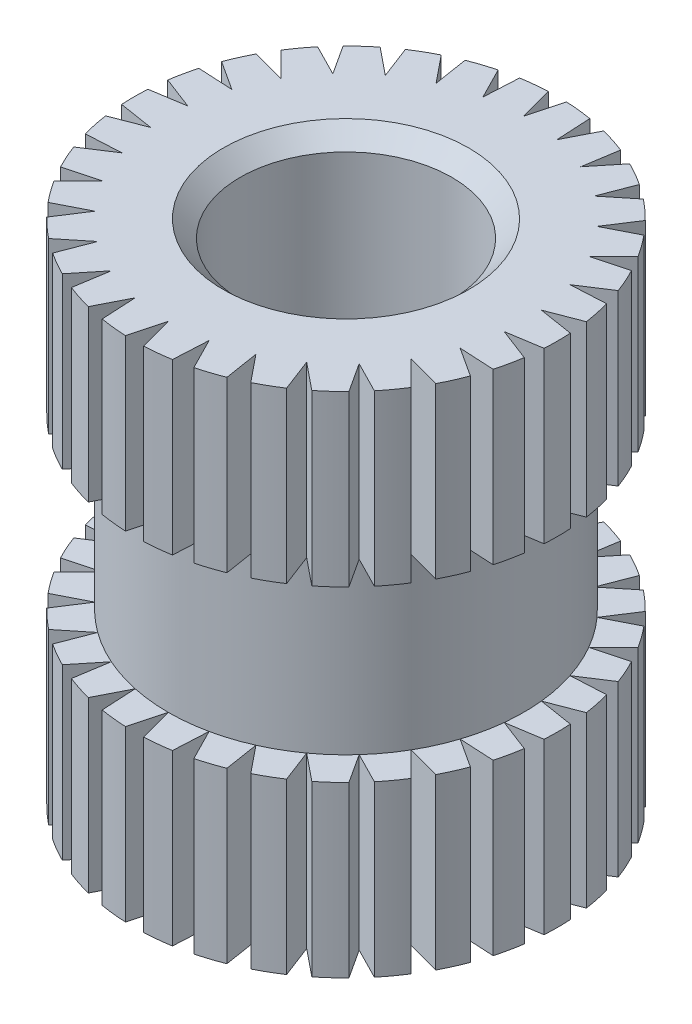
SolidWorks part; units mm, degrees
material "Brass"
ref_plane "Front" through (0, 0, 0) normal (0, 0, 1) x (1, 0, 0)
ref_plane "Top" through (0, 0, 0) normal (0, 1, 0) x (1, 0, 0)
ref_plane "Right" through (0, 0, 0) normal (1, 0, 0) x (0, 0, -1)
sketch "Sketch1" plane through (0, 0, 0) normal (1, 0, 0) x (0, 0, -1)
  line L0 (0, 5.7394) -> (0, 0) construction
  line L1 (0, 0) -> (3.7148, 0) construction
  line L2 (2.1, -1) -> (2.5, -1)
  line L3 (1.25, 3) -> (2.5, 3)
  line L4 (1.25, 3) -> (1.25, -3)
  line L5 (2.5, -3) -> (2.5, -1)
  line L6 (2.5, 3) -> (2.5, 1)
  line L7 (2.1, 1) -> (2.5, 1)
  line L8 (2.1, 1) -> (2.1, -1)
  line L9 (1.25, -3) -> (2.5, -3)
  point P10 (2.1, 0)
  point P14 (1.25, 0)
  dimension "D1" = 2.5
  dimension "D2" = 3
  dimension "D3" = 5
  dimension "D4" = 4.2
  dimension "D5" = 2
revolve "Revolve1" add sketch "Sketch1" angle 360 about L0
cosmetic thread "Cosmetic Thread1" parameters "D2"=3
sketch "Sketch2" plane through (0, 3, 0) normal (0, 1, 0) x (1, 0, 0)
  line L0 (-0.2412, 3) -> (0, 2.1)
  line L1 (0, 2.1) -> (0.2412, 3)
  line L2 (0.2412, 3) -> (-0.2412, 3)
  line L3 (0, 0) -> (0, 3.2578) construction
  circle A0 centre (0, 0) radius 2.1 construction
  dimension "D1" = 30
  dimension "D2" = 3
extrude "Cut-Extrude1" cut sketch "Sketch2" against normal blind 10
pattern_circular "CirPattern1" count 30 over 360 about axis through (0, 0, 0) along (0, 1, 0) of "Cut-Extrude1"
chamfer "Chamfer1" distance 0.2 angle 45 2 edges at (0, -3, 1.25) (0, 3, 1.25)
